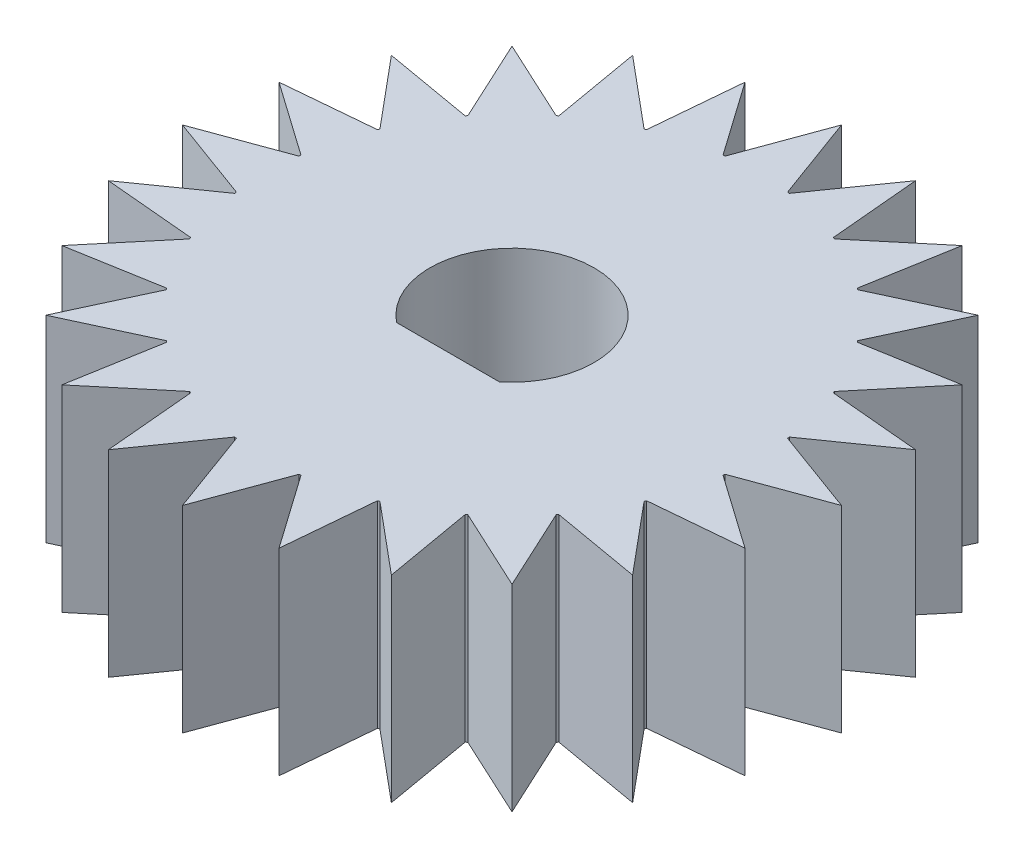
SolidWorks part; units mm, degrees
ref_plane "Спереди" through (0, 0, 0) normal (0, 0, 1) x (1, 0, 0)
ref_plane "Сверху" through (0, 0, 0) normal (0, 1, 0) x (1, 0, 0)
ref_plane "Справа" through (0, 0, 0) normal (1, 0, 0) x (0, 0, -1)
sketch "Эскиз1" plane through (0, 0, 0) normal (0, 1, 0) x (1, 0, 0)
  line L2 (-0.9495, 7.4397) -> (0, 10.03)
  line L3 (2.8427, 6.9404) -> (2.596, 9.6882)
  line L222 (-1.5644, -1.95) -> (1.5644, -1.95)
  line L225 (0.9495, 7.4397) -> (0, 10.03)
  line L226 (1.0084, 7.4319) -> (2.596, 9.6882)
  line L227 (4.5421, 5.9682) -> (5.015, 8.6862)
  line L228 (2.8975, 6.9177) -> (5.015, 8.6862)
  line L229 (5.932, 4.5892) -> (7.0923, 7.0923)
  line L230 (4.5892, 5.932) -> (7.0923, 7.0923)
  line L231 (6.9177, 2.8975) -> (8.6862, 5.015)
  line L232 (5.9682, 4.5421) -> (8.6862, 5.015)
  line L233 (7.4319, 1.0084) -> (9.6882, 2.596)
  line L234 (6.9404, 2.8427) -> (9.6882, 2.596)
  line L235 (7.4397, -0.9495) -> (10.03, 0)
  line L236 (7.4397, 0.9495) -> (10.03, 0)
  line L237 (6.9404, -2.8427) -> (9.6882, -2.596)
  line L238 (7.4319, -1.0084) -> (9.6882, -2.596)
  line L239 (5.9682, -4.5421) -> (8.6862, -5.015)
  line L240 (6.9177, -2.8975) -> (8.6862, -5.015)
  line L241 (4.5892, -5.932) -> (7.0923, -7.0923)
  line L242 (5.932, -4.5892) -> (7.0923, -7.0923)
  line L243 (2.8975, -6.9177) -> (5.015, -8.6862)
  line L244 (4.5421, -5.9682) -> (5.015, -8.6862)
  line L245 (1.0084, -7.4319) -> (2.596, -9.6882)
  line L246 (2.8427, -6.9404) -> (2.596, -9.6882)
  line L247 (-0.9495, -7.4397) -> (0, -10.03)
  line L248 (0.9495, -7.4397) -> (0, -10.03)
  line L249 (-2.8427, -6.9404) -> (-2.596, -9.6882)
  line L250 (-1.0084, -7.4319) -> (-2.596, -9.6882)
  line L251 (-4.5421, -5.9682) -> (-5.015, -8.6862)
  line L252 (-2.8975, -6.9177) -> (-5.015, -8.6862)
  line L253 (-5.932, -4.5892) -> (-7.0923, -7.0923)
  line L254 (-4.5892, -5.932) -> (-7.0923, -7.0923)
  line L255 (-6.9177, -2.8975) -> (-8.6862, -5.015)
  line L256 (-5.9682, -4.5421) -> (-8.6862, -5.015)
  line L257 (-7.4319, -1.0084) -> (-9.6882, -2.596)
  line L258 (-6.9404, -2.8427) -> (-9.6882, -2.596)
  line L259 (-7.4397, 0.9495) -> (-10.03, 0)
  line L260 (-7.4397, -0.9495) -> (-10.03, 0)
  line L261 (-6.9404, 2.8427) -> (-9.6882, 2.596)
  line L262 (-7.4319, 1.0084) -> (-9.6882, 2.596)
  line L263 (-5.9682, 4.5421) -> (-8.6862, 5.015)
  line L264 (-6.9177, 2.8975) -> (-8.6862, 5.015)
  line L265 (-4.5892, 5.932) -> (-7.0923, 7.0923)
  line L266 (-5.932, 4.5892) -> (-7.0923, 7.0923)
  line L267 (-2.8975, 6.9177) -> (-5.015, 8.6862)
  line L268 (-4.5421, 5.9682) -> (-5.015, 8.6862)
  line L269 (-1.0084, 7.4319) -> (-2.596, 9.6882)
  line L270 (-2.8427, 6.9404) -> (-2.596, 9.6882)
  arc A6 (-1.5644, -1.95) -> (1.5644, -1.95) centre (0, 0) cw
  circle A7 centre (0, 0) radius 7.5
  point P80 (0, 0)
  point P158 (0, 0)
  point P224 (0, 0)
  dimension "D1" = 24
extrude "Бобышка-Вытянуть2" add sketch "Эскиз1" along normal blind 6 contours A7 L222 A6 | A7 L225 L2 | A7 L269 L270 | A7 L267 L268 | A7 L265 L266 | A7 L263 L264 | A7 L261 L262 | A7 L259 L260 | A7 L257 L258 | A7 L255 L256 | A7 L253 L254 | A7 L251 L252 | A7 L249 L250 | A7 L247 L248 | A7 L245 L246 | A7 L243 L244 | A7 L241 L242 | A7 L239 L240 | A7 L237 L238 | A7 L235 L236 | A7 L233 L234 | A7 L231 L232 | A7 L229 L230 | A7 L227 L228 | A7 L3 L226
